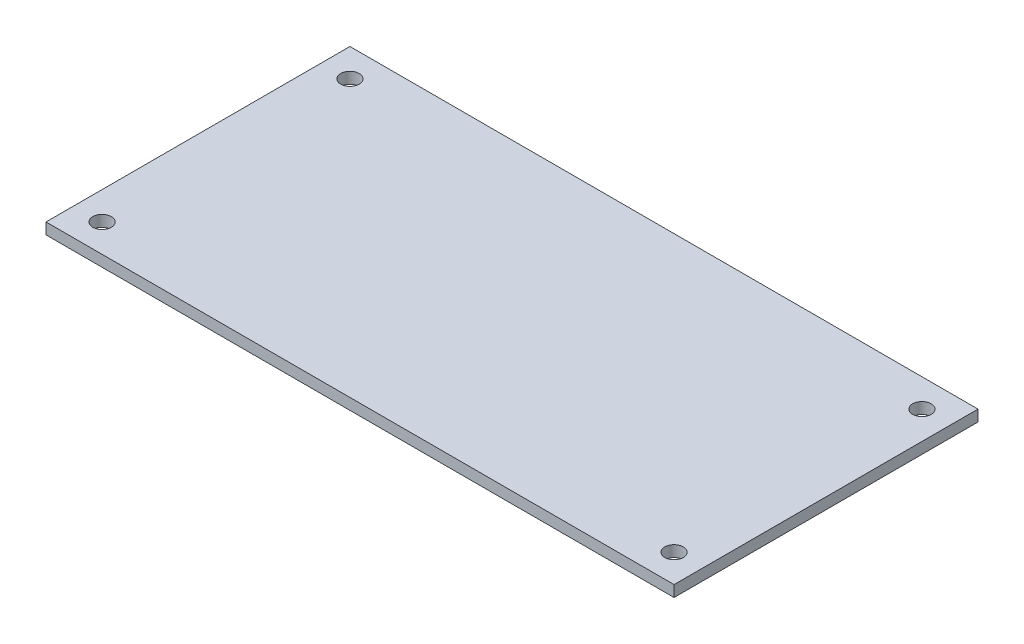
SolidWorks part; units mm, degrees
ref_plane "前视基准面" through (0, 0, 0) normal (0, 0, 1) x (1, 0, 0)
ref_plane "上视基准面" through (0, 0, 0) normal (0, 1, 0) x (1, 0, 0)
ref_plane "右视基准面" through (0, 0, 0) normal (1, 0, 0) x (0, 0, -1)
sketch "草图1" plane through (0, 0, 0) normal (0, 1, 0) x (1, 0, 0)
  line L1 (0, 0) -> (112, 0)
  line L2 (0, 0) -> (0, -54.2)
  line L3 (0, -54.2) -> (112, -54.2)
  line L4 (112, 0) -> (112, -54.2)
  circle A0 centre (5, -5) radius 1.65
  circle A1 centre (107, -5) radius 1.65
  circle A2 centre (107, -49.2) radius 1.65
  circle A3 centre (5, -49.2) radius 1.65
  dimension "D3" = 3.3
  dimension "D1" = 112
  dimension "D2" = 54.2
  dimension "D4" = 5
  dimension "D5" = 5
  dimension "D6" = 5
  dimension "D7" = 5
  dimension "D8" = 5
  dimension "D9" = 5
  dimension "D10" = 5
  dimension "D11" = 5
extrude "凸台-拉伸1" add sketch "草图1" along normal blind 2
